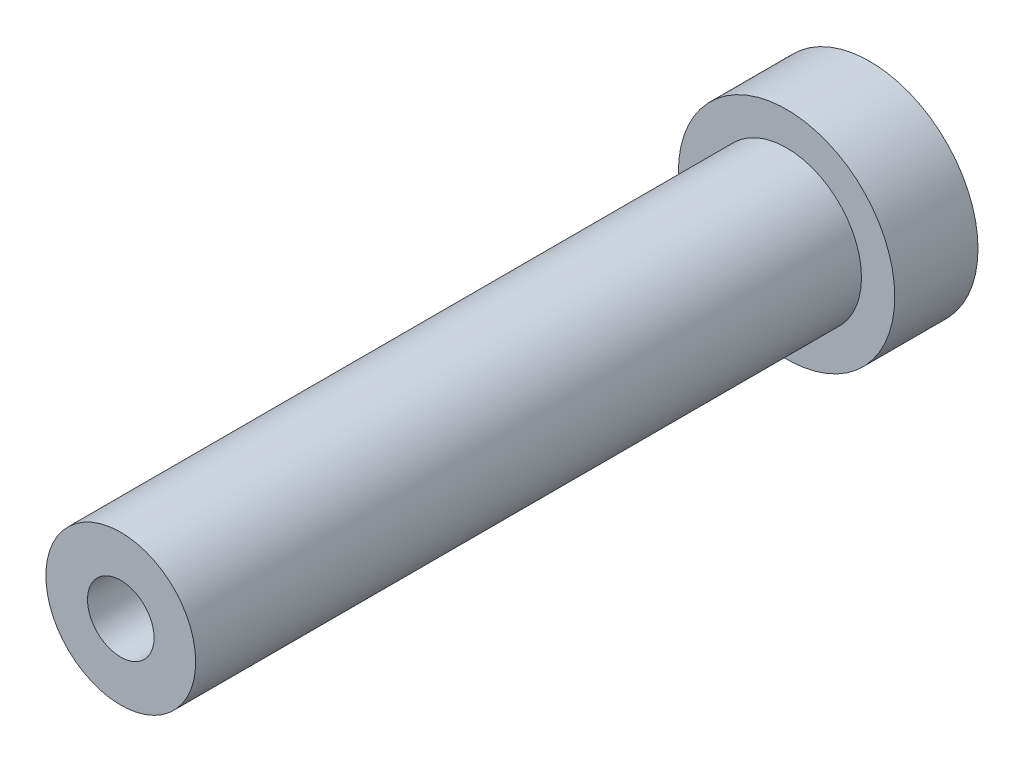
SolidWorks part; units mm, degrees
ref_plane "Front Plane" through (0, 0, 0) normal (0, 0, 1) x (1, 0, 0)
ref_plane "Top Plane" through (0, 0, 0) normal (0, 1, 0) x (1, 0, 0)
ref_plane "Right Plane" through (0, 0, 0) normal (1, 0, 0) x (0, 0, -1)
sketch "Sketch1" plane through (0, 0, 0) normal (0, 0, 1) x (1, 0, 0)
  circle A0 centre (0, 0) radius 4.5
  circle A1 centre (0, 0) radius 2
  dimension "D1" = 4
  dimension "D2" = 9
extrude "Boss-Extrude1" add sketch "Sketch1" along normal blind 40
sketch "Sketch2" plane through (0, 0, 0) normal (0, 0, -1) x (-1, 0, 0)
  circle A0 centre (0, 0) radius 6.5
  dimension "D1" = 13
extrude "Boss-Extrude2" add sketch "Sketch2" along normal blind 5
